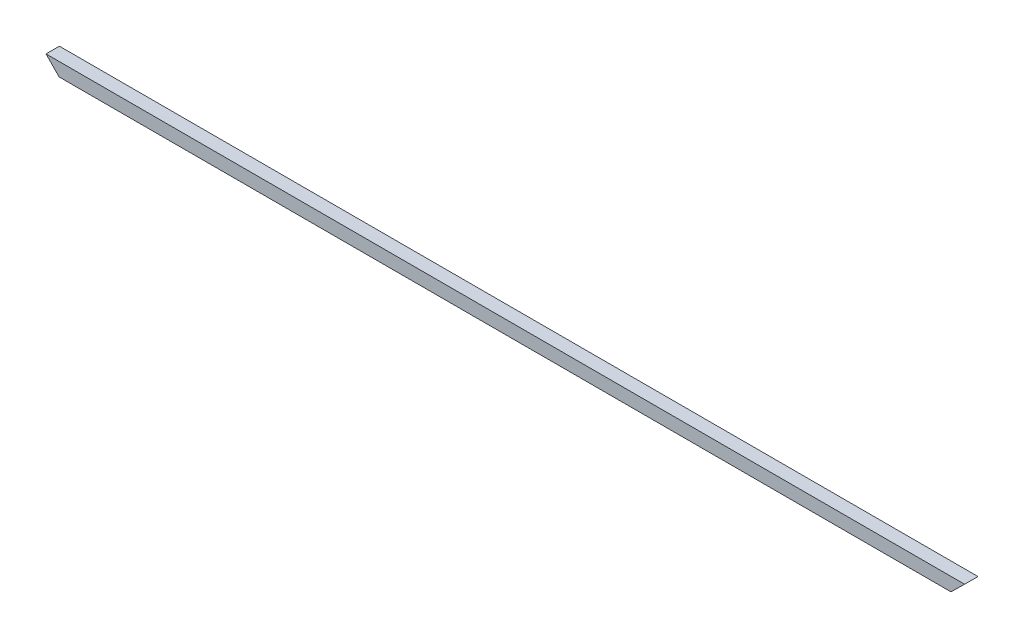
SolidWorks part; units mm, degrees
ref_plane "Front Plane" through (0, 0, 0) normal (0, 0, 1) x (1, 0, 0)
ref_plane "Top Plane" through (0, 0, 0) normal (0, 1, 0) x (1, 0, 0)
ref_plane "Right Plane" through (0, 0, 0) normal (1, 0, 0) x (0, 0, -1)
sketch "Sketch2" plane through (0, 0, 0) normal (0, 0, 1) x (1, 0, 0)
  line L0 (-2719.6252, 0) -> (24.0748, 0)
  line L1 (55, 0) -> (-55, 0) construction
  line L2 (24.0748, 0) -> (-16.7718, -40)
  line L3 (-16.7718, -40) -> (-2680.4543, -40)
  line L4 (-2680.4543, -40) -> (-2719.6252, 0)
  dimension "D1" = 45.6
  dimension "D2" = 44.4
  dimension "D3" = 2743.7
  dimension "D4" = 40
extrude "Boss-Extrude1" add sketch "Sketch2" along normal blind 40
